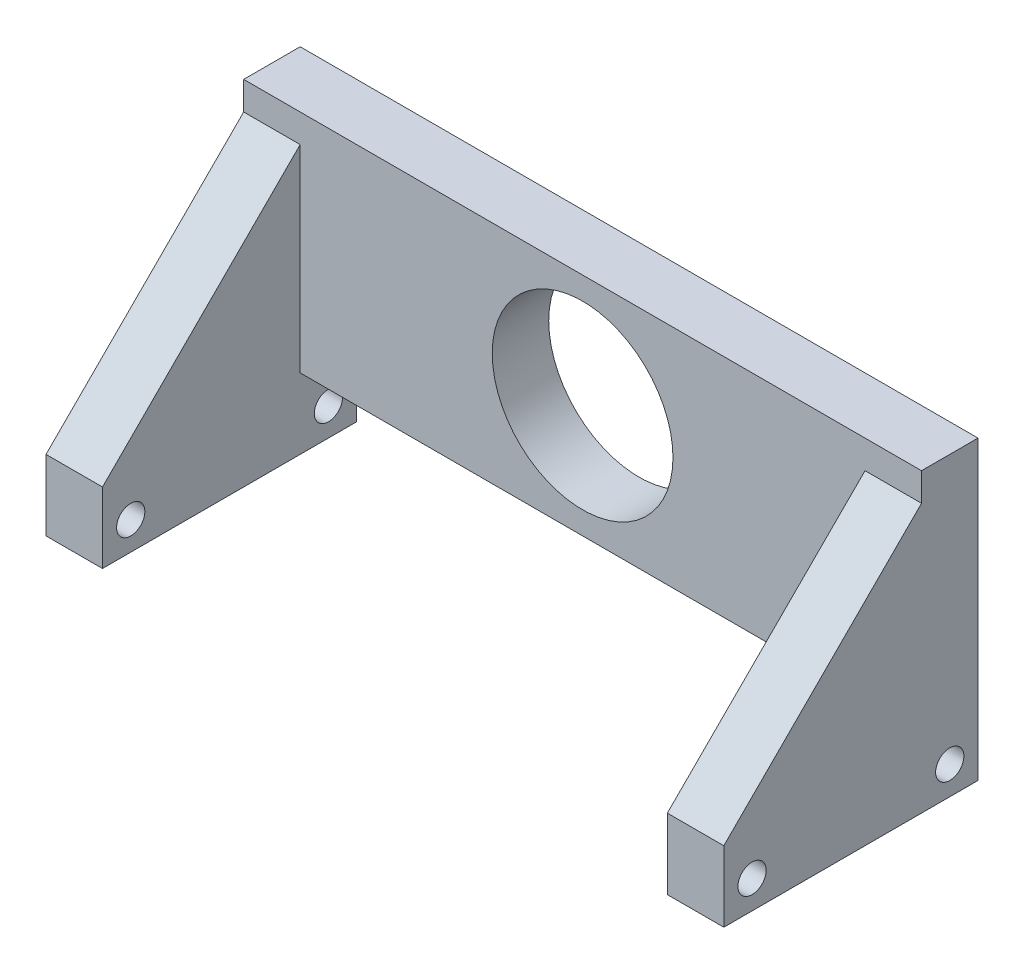
SolidWorks part; units mm, degrees
ref_plane "Alzado" through (0, 0, 0) normal (0, 0, 1) x (1, 0, 0)
ref_plane "Planta" through (0, 0, 0) normal (0, 1, 0) x (1, 0, 0)
ref_plane "Vista lateral" through (0, 0, 0) normal (1, 0, 0) x (0, 0, -1)
sketch "Sketch2" plane through (0, 0, 0) normal (0, 0, 1) x (1, 0, 0)
  line L1 (-50, 20) -> (50, 20)
  line L2 (-50, 20) -> (-50, -20)
  line L3 (-50, -20) -> (50, -20)
  line L4 (50, 20) -> (50, -20)
  line L5 (-50, 20) -> (50, -20) construction
  line L6 (-50, -20) -> (50, 20) construction
  point P0 (0, 0)
  dimension "D1" = 100
  dimension "D2" = 40
extrude "Boss-Extrude1" add sketch "Sketch2" along normal blind 10
sketch "Sketch3" plane through (0, 0, 10) normal (0, 0, 1) x (1, 0, 0)
  circle A0 centre (0, 0) radius 7.5
  dimension "D1" = 15
extrude "Cut-Extrude1" cut sketch "Sketch3" against normal through all
sketch "Sketch4" plane through (0, 0, 10) normal (0, 0, 1) x (1, 0, 0)
  circle A0 centre (0, 0) radius 16
  dimension "D1" = 32
extrude "Cut-Extrude2" cut sketch "Sketch4" against normal through all
sketch "Sketch5" plane through (-50, 0, 0) normal (-1, 0, 0) x (0, 0, 1)
  line L0 (10, 20) -> (10, -20) construction
  line L1 (0, 20) -> (10, 20)
  line L2 (0, 20) -> (0, -32.5)
  line L3 (0, -32.5) -> (10, -32.5)
  line L4 (10, 20) -> (10, 15)
  line L5 (10, -20) -> (0, -20) construction
  line L6 (10, -32.5) -> (45, -32.5)
  line L7 (45, -32.5) -> (45, -20)
  line L8 (45, -20) -> (10, 15)
  line L9 (10, 15) -> (10, -32.5) construction
  circle A0 centre (5, -27.5) radius 2.5
  circle A1 centre (40, -27.5) radius 2.5
  point P9 (5, -32.5)
  dimension "D1" = 5
  dimension "D3" = 5
  dimension "D4" = 5
  dimension "D2" = 7.5
  dimension "D5" = 35
  dimension "D6" = 135
extrude "Boss-Extrude2" add sketch "Sketch5" along normal blind 10
mirror "Mirror1" about plane through (0, 0, 0) normal (1, 0, 0) of "Boss-Extrude2"
